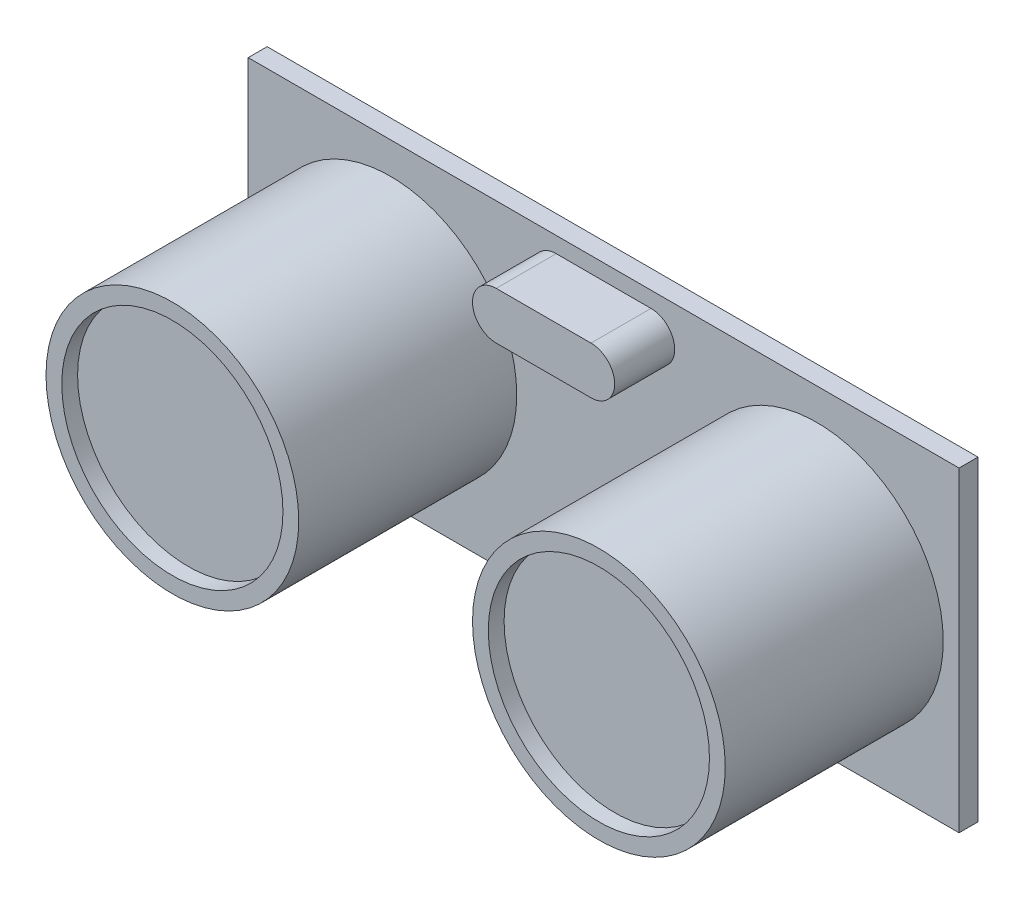
SolidWorks part; units mm, degrees
ref_plane "前视基准面" through (0, 0, 0) normal (0, 0, 1) x (1, 0, 0)
ref_plane "上视基准面" through (0, 0, 0) normal (0, 1, 0) x (1, 0, 0)
ref_plane "右视基准面" through (0, 0, 0) normal (1, 0, 0) x (0, 0, -1)
other "Configuration Table"
sketch "草图1" plane through (0, 0, 0) normal (0, 0, 1) x (1, 0, 0)
  line L1 (-22.5, -10) -> (22.5, -10)
  line L2 (-22.5, -10) -> (-22.5, 10)
  line L3 (-22.5, 10) -> (22.5, 10)
  line L4 (22.5, -10) -> (22.5, 10)
  line L5 (-22.5, -10) -> (22.5, 10) construction
  line L6 (-22.5, 10) -> (22.5, -10) construction
  point P0 (0, 0)
  dimension "D1" = 45
  dimension "D2" = 20
extrude "凸台-拉伸1" add sketch "草图1" along normal blind 1.2
sketch "草图2" plane through (0, 0, 0) normal (0, 0, 1) x (1, 0, 0)
  line L0 (-13.5, 0) -> (13.5, 0) construction
  circle A0 centre (-13.5, 0) radius 8
  circle A1 centre (13.5, 0) radius 8
  point P4 (0, 0)
  dimension "D2" = 16
  dimension "D3" = 16
  dimension "D1" = 27
extrude "凸台-拉伸2" add sketch "草图2" along normal blind 15
sketch "草图3" plane through (0, 0, 0) normal (0, 0, 1) x (1, 0, 0)
  line L0 (-3, 7.5) -> (3, 7.5) construction
  line L1 (-3, 9) -> (3, 9)
  line L2 (-3, 6) -> (3, 6)
  line L3 (22.5, 10) -> (-22.5, 10) construction
  arc A0 (-3, 9) -> (-3, 6) centre (-3, 7.5) ccw
  arc A1 (3, 6) -> (3, 9) centre (3, 7.5) ccw
  point P2 (0, 7.5)
  point P7 (0, 0)
  dimension "D1" = 1.5
  dimension "D2" = 6
  dimension "D3" = 1
extrude "凸台-拉伸3" add sketch "草图3" along normal blind 5
sketch "草图5" plane through (0, 0, 0) normal (0, 0, 1) x (1, 0, 0)
  line L0 (0, -1000) -> (0, 49000) construction
  circle A0 centre (-13.5, 0) radius 7
  circle A1 centre (-13.5, 0) radius 8 construction
  circle A2 centre (13.5, 0) radius 7
  dimension "D1" = 14
extrude "切除-拉伸1" cut sketch "草图5" against normal blind 1 from surface at 15 starting at face at (-5.5, 0, 15)
